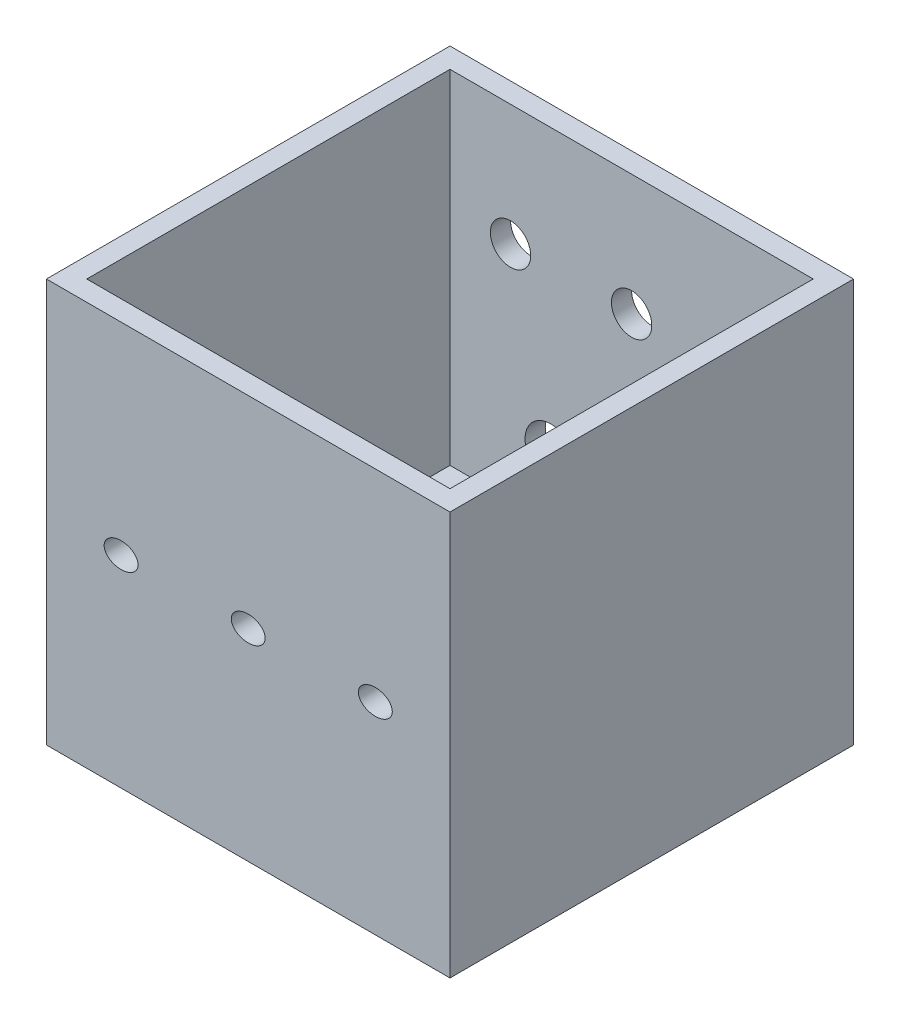
SolidWorks part; units mm, degrees
ref_plane "Front Plane" through (0, 0, 0) normal (0, 0, 1) x (1, 0, 0)
ref_plane "Top Plane" through (0, 0, 0) normal (0, 1, 0) x (1, 0, 0)
ref_plane "Right Plane" through (0, 0, 0) normal (1, 0, 0) x (0, 0, -1)
sketch "Sketch1" plane through (0, 0, 0) normal (0, 0, 1) x (1, 0, 0)
  line L1 (-31.75, -31.75) -> (31.75, -31.75)
  line L2 (-31.75, -31.75) -> (-31.75, 31.75)
  line L3 (-31.75, 31.75) -> (31.75, 31.75)
  line L4 (31.75, -31.75) -> (31.75, 31.75)
  line L5 (-31.75, -31.75) -> (31.75, 31.75) construction
  line L6 (-31.75, 31.75) -> (31.75, -31.75) construction
  point P0 (0, 0)
  dimension "D1" = 63.5
  dimension "D2" = 63.5
extrude "Boss-Extrude1" add sketch "Sketch1" along normal blind 63.5
sketch "Sketch2" plane through (0, 0, 63.5) normal (0, 0, 1) x (1, 0, 0)
  line L0 (-31.75, 0) -> (31.75, 0) construction
  line L1 (-31.75, 31.75) -> (-31.75, -31.75) construction
  line L2 (31.75, -31.75) -> (31.75, 31.75) construction
  ellipse E0 centre (0, 0) end of major axis (2.667, 0) minor radius 1.9685
  ellipse E1 centre (20, 0) end of major axis (22.667, 0) minor radius 1.9685
  ellipse E2 centre (-20, 0) end of major axis (-17.333, 0) minor radius 1.9685
  dimension "D1" = 5.334
  dimension "D2" = 5.334
  dimension "D3" = 5.334
  dimension "D4" = 3.937
  dimension "D5" = 3.937
  dimension "D6" = 3.937
  dimension "D7" = 20
  dimension "D8" = 20
extrude "Cut-Extrude1" cut sketch "Sketch2" against normal blind 3.175
sketch "Sketch3" plane through (0, 31.75, 0) normal (0, 1, 0) x (1, 0, 0)
  line L0 (0, 0) -> (0, -63.5) construction
  line L1 (31.75, 0) -> (-31.75, 0) construction
  line L2 (31.75, -63.5) -> (-31.75, -63.5) construction
  line L3 (0, -63.5) -> (31.75, -31.75) construction
  line L4 (31.75, -63.5) -> (31.75, 0) construction
  line L5 (31.75, -31.75) -> (-31.75, -31.75) construction
  line L6 (-31.75, -63.5) -> (-31.75, 0) construction
  line L8 (-28.575, -60.325) -> (28.575, -60.325)
  line L9 (-28.575, -60.325) -> (-28.575, -3.175)
  line L10 (-28.575, -3.175) -> (28.575, -3.175)
  line L11 (28.575, -60.325) -> (28.575, -3.175)
  line L12 (-28.575, -60.325) -> (28.575, -3.175) construction
  line L13 (-28.575, -3.175) -> (28.575, -60.325) construction
  point P6 (0, -31.75)
  dimension "D1" = 3.175
  dimension "D2" = 3.175
extrude "Cut-Extrude2" cut sketch "Sketch3" against normal blind 53.975
sketch "Sketch4" plane through (0, 0, 0) normal (0, 0, -1) x (-1, 0, 0)
  line L0 (-31.75, -12.7) -> (31.75, -12.7) construction
  line L1 (-31.75, -31.75) -> (-31.75, 31.75) construction
  line L2 (31.75, 31.75) -> (31.75, -31.75) construction
  line L3 (31.75, -31.75) -> (-31.75, -31.75) construction
  circle A0 centre (-12.5984, -12.7) radius 4.064
  circle A1 centre (12.7, -12.7) radius 4.064
  dimension "D3" = 8.128
  dimension "D4" = 8.128
  dimension "D1" = 19.1516
  dimension "D2" = 19.05
  dimension "D5" = 19.05
extrude "Cut-Extrude3" cut sketch "Sketch4" against normal up to next
sketch "Sketch5" plane through (0, 0, 0) normal (0, 0, -1) x (-1, 0, 0)
  line L0 (-31.75, 12.7) -> (31.75, 12.7) construction
  line L1 (-31.75, -31.75) -> (-31.75, 31.75) construction
  line L2 (31.75, 31.75) -> (31.75, -31.75) construction
  line L3 (-31.75, 31.75) -> (31.75, 31.75) construction
  circle A0 centre (-19.05, 12.7) radius 3.175
  circle A1 centre (0, 12.7) radius 3.175
  circle A2 centre (19.05, 12.7) radius 3.175
  dimension "D1" = 6.35
  dimension "D2" = 6.35
  dimension "D3" = 6.35
  dimension "D4" = 19.05
  dimension "D5" = 19.05
  dimension "D6" = 19.05
extrude "Cut-Extrude4" cut sketch "Sketch5" against normal up to next
